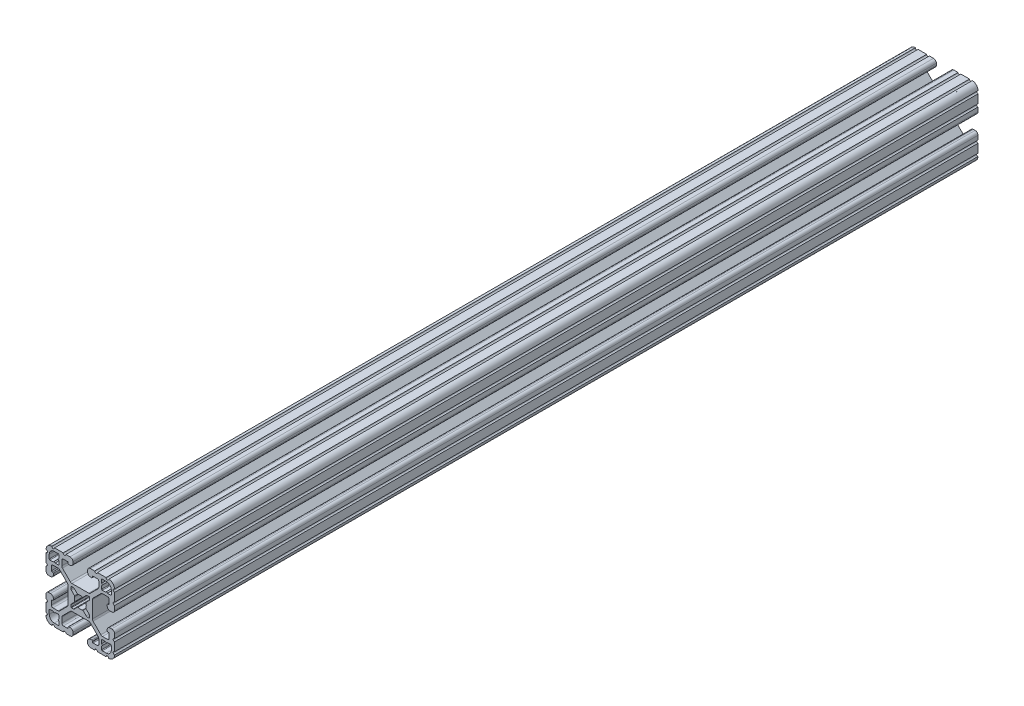
SolidWorks part; units mm, degrees
ref_plane "Front Plane" through (0, 0, 0) normal (0, 0, 1) x (1, 0, 0)
ref_plane "Top Plane" through (0, 0, 0) normal (0, 1, 0) x (1, 0, 0)
ref_plane "Right Plane" through (0, 0, 0) normal (1, 0, 0) x (0, 0, -1)
ref_plane "Plane1" through (0, 0, -304.8) normal (0, 0, -1) x (-1, 0, 0)
sketch "Sketch1" plane through (0, 0, -304.8) normal (0, 0, -1) x (-1, 0, 0)
  line L0 (-12.2479, 11.8669) -> (-14.0194, 11.8669)
  line L1 (-14.0212, 11.8676) -> (-14.5575, 12.4039)
  line L2 (-14.5611, 12.4039) -> (-15.0973, 11.8676)
  line L3 (-15.0991, 11.8669) -> (-16.8707, 11.8669)
  line L4 (-17.2517, 12.2479) -> (-17.2517, 14.4577)
  line L5 (-14.4577, 17.2517) -> (-12.2479, 17.2517)
  line L6 (-11.8669, 16.8707) -> (-11.8669, 15.0991)
  line L7 (-11.8676, 15.0973) -> (-12.4039, 14.5611)
  line L8 (-12.4039, 14.5575) -> (-11.8676, 14.0213)
  line L9 (-11.8669, 14.0195) -> (-11.8669, 12.2479)
  line L10 (-11.8669, -12.2479) -> (-11.8669, -14.0194)
  line L11 (-11.8676, -14.0212) -> (-12.4039, -14.5575)
  line L12 (-12.4039, -14.5611) -> (-11.8676, -15.0973)
  line L13 (-11.8669, -15.0991) -> (-11.8669, -16.8707)
  line L14 (-12.2479, -17.2517) -> (-14.4577, -17.2517)
  line L15 (-17.2517, -14.4577) -> (-17.2517, -12.2479)
  line L16 (-16.8707, -11.8669) -> (-15.0991, -11.8669)
  line L17 (-15.0973, -11.8676) -> (-14.5611, -12.4039)
  line L18 (-14.5575, -12.4039) -> (-14.0213, -11.8676)
  line L19 (-14.0195, -11.8669) -> (-12.2479, -11.8669)
  line L20 (12.2479, -11.8669) -> (14.0194, -11.8669)
  line L21 (14.0212, -11.8676) -> (14.5575, -12.4039)
  line L22 (14.5611, -12.4039) -> (15.0973, -11.8676)
  line L23 (15.0991, -11.8669) -> (16.8707, -11.8669)
  line L24 (17.2517, -12.2479) -> (17.2517, -14.4577)
  line L25 (14.4577, -17.2517) -> (12.2479, -17.2517)
  line L26 (11.8669, -16.8707) -> (11.8669, -15.0991)
  line L27 (11.8676, -15.0973) -> (12.4039, -14.5611)
  line L28 (12.4039, -14.5575) -> (11.8676, -14.0213)
  line L29 (11.8669, -14.0195) -> (11.8669, -12.2479)
  line L30 (11.8669, 12.2479) -> (11.8669, 14.0194)
  line L31 (11.8676, 14.0212) -> (12.4039, 14.5575)
  line L32 (12.4039, 14.5611) -> (11.8676, 15.0973)
  line L33 (11.8669, 15.0991) -> (11.8669, 16.8707)
  line L34 (12.2479, 17.2517) -> (14.4577, 17.2517)
  line L35 (17.2517, 14.4577) -> (17.2517, 12.2479)
  line L36 (16.8707, 11.8669) -> (15.0991, 11.8669)
  line L37 (15.0973, 11.8676) -> (14.5611, 12.4039)
  line L38 (14.5575, 12.4039) -> (14.0213, 11.8676)
  line L39 (14.0195, 11.8669) -> (12.2479, 11.8669)
  line L40 (1.5823, 3.1988) -> (3.2921, 4.9085)
  line L41 (3.9207, 5.1689) -> (4.9149, 5.1689)
  line L42 (5.1689, 4.9149) -> (5.1689, 3.9207)
  line L43 (4.9085, 3.2921) -> (3.1988, 1.5823)
  line L44 (3.1988, -1.5823) -> (4.9085, -3.2921)
  line L45 (5.1689, -3.9207) -> (5.1689, -4.9149)
  line L46 (4.9149, -5.1689) -> (3.9207, -5.1689)
  line L47 (3.2921, -4.9085) -> (1.5823, -3.1988)
  line L48 (-1.5823, -3.1988) -> (-3.2921, -4.9085)
  line L49 (-3.9207, -5.1689) -> (-4.9149, -5.1689)
  line L50 (-5.1689, -4.9149) -> (-5.1689, -3.9207)
  line L51 (-4.9085, -3.2921) -> (-3.1988, -1.5823)
  line L52 (-3.1988, 1.5823) -> (-4.9085, 3.2921)
  line L53 (-5.1689, 3.9207) -> (-5.1689, 4.9149)
  line L54 (-4.9149, 5.1689) -> (-3.9207, 5.1689)
  line L55 (-3.2921, 4.9085) -> (-1.5823, 3.1988)
  line L56 (-6.731, -15.3661) -> (-6.731, -15.6969)
  line L57 (-7.1122, -16.0782) -> (-9.3968, -16.0782)
  line L58 (-10.287, -15.1881) -> (-10.2871, -12.38)
  line L59 (-9.9142, -11.481) -> (-5.5384, -7.1147)
  line L60 (-4.6414, -6.7437) -> (4.6689, -6.7437)
  line L61 (5.5659, -7.1147) -> (9.9142, -11.4535)
  line L62 (10.2871, -12.3526) -> (10.287, -15.1881)
  line L63 (9.3968, -16.0782) -> (7.1122, -16.0782)
  line L64 (6.731, -15.6969) -> (6.731, -15.3661)
  line L65 (6.3498, -14.9848) -> (5.6531, -14.9848)
  line L66 (4.0778, -16.5601) -> (4.0778, -17.4747)
  line L67 (5.6531, -19.05) -> (7.9756, -19.05)
  line L68 (9.4996, -19.05) -> (14.3256, -19.05)
  line L69 (19.05, -14.2981) -> (19.05, -9.4996)
  line L70 (19.05, -7.9756) -> (19.05, -5.6531)
  line L71 (17.4747, -4.0778) -> (16.5601, -4.0778)
  line L72 (14.9848, -5.6531) -> (14.9848, -6.3498)
  line L73 (15.3661, -6.731) -> (15.6969, -6.731)
  line L74 (16.0782, -7.1122) -> (16.0782, -9.3968)
  line L75 (15.1881, -10.287) -> (12.38, -10.2871)
  line L76 (11.481, -9.9142) -> (7.1147, -5.5384)
  line L77 (6.7437, -4.6414) -> (6.7437, 4.6689)
  line L78 (7.1147, 5.5659) -> (11.4535, 9.9142)
  line L79 (12.3526, 10.2871) -> (15.1881, 10.287)
  line L80 (16.0782, 9.3968) -> (16.0782, 7.1122)
  line L81 (15.6969, 6.731) -> (15.3661, 6.731)
  line L82 (14.9848, 6.3498) -> (14.9848, 5.6531)
  line L83 (16.5601, 4.0778) -> (17.4747, 4.0778)
  line L84 (19.05, 5.6531) -> (19.05, 7.9756)
  line L85 (19.05, 9.4996) -> (19.05, 14.3256)
  line L86 (14.2981, 19.05) -> (9.4996, 19.05)
  line L87 (7.9756, 19.05) -> (5.6531, 19.05)
  line L88 (4.0778, 17.4747) -> (4.0778, 16.5601)
  line L89 (5.6531, 14.9848) -> (6.3498, 14.9848)
  line L90 (6.731, 15.3661) -> (6.731, 15.6969)
  line L91 (7.1122, 16.0782) -> (9.3968, 16.0782)
  line L92 (10.287, 15.1881) -> (10.2871, 12.38)
  line L93 (9.9142, 11.481) -> (5.5384, 7.1147)
  line L94 (4.6414, 6.7437) -> (-4.6689, 6.7437)
  line L95 (-5.5659, 7.1147) -> (-9.9142, 11.4535)
  line L96 (-10.2871, 12.3526) -> (-10.287, 15.1881)
  line L97 (-9.3968, 16.0782) -> (-7.1122, 16.0782)
  line L98 (-6.731, 15.6969) -> (-6.731, 15.3661)
  line L99 (-6.3498, 14.9848) -> (-5.6531, 14.9848)
  line L100 (-4.0778, 16.5601) -> (-4.0778, 17.4747)
  line L101 (-5.6531, 19.05) -> (-7.9756, 19.05)
  line L102 (-9.4996, 19.05) -> (-14.3256, 19.05)
  line L103 (-19.05, 14.2981) -> (-19.05, 9.4996)
  line L104 (-19.05, 7.9756) -> (-19.05, 5.6531)
  line L105 (-17.4747, 4.0778) -> (-16.5601, 4.0778)
  line L106 (-14.9848, 5.6531) -> (-14.9848, 6.3498)
  line L107 (-15.3661, 6.731) -> (-15.6969, 6.731)
  line L108 (-16.0782, 7.1122) -> (-16.0782, 9.3968)
  line L109 (-15.1881, 10.287) -> (-12.38, 10.2871)
  line L110 (-11.481, 9.9142) -> (-7.1147, 5.5384)
  line L111 (-6.7437, 4.6414) -> (-6.7437, -4.6689)
  line L112 (-7.1147, -5.5659) -> (-11.4535, -9.9142)
  line L113 (-12.3526, -10.2871) -> (-15.1881, -10.287)
  line L114 (-16.0782, -9.3968) -> (-16.0782, -7.1122)
  line L115 (-15.6969, -6.731) -> (-15.3661, -6.731)
  line L116 (-14.9848, -6.3498) -> (-14.9848, -5.6531)
  line L117 (-16.5601, -4.0778) -> (-17.4747, -4.0778)
  line L118 (-19.05, -5.6531) -> (-19.05, -7.9756)
  line L119 (-19.05, -9.4996) -> (-19.05, -14.3256)
  line L120 (-14.2981, -19.05) -> (-9.4996, -19.05)
  line L121 (-7.9756, -19.05) -> (-5.6531, -19.05)
  line L122 (-4.0778, -17.4747) -> (-4.0778, -16.5601)
  line L123 (-5.6531, -14.9848) -> (-6.3498, -14.9848)
  arc A0 (-14.0194, 11.8669) -> (-14.0212, 11.8676) centre (-14.0194, 11.8694) cw
  arc A1 (-14.5575, 12.4039) -> (-14.5611, 12.4039) centre (-14.5593, 12.4021) ccw
  arc A2 (-15.0973, 11.8676) -> (-15.0991, 11.8669) centre (-15.0991, 11.8694) cw
  arc A3 (-16.8707, 11.8669) -> (-17.2517, 12.2479) centre (-16.8707, 12.2479) cw
  arc A4 (-17.2517, 14.4577) -> (-14.4577, 17.2517) centre (-14.4577, 14.4577) cw
  arc A5 (-12.2479, 17.2517) -> (-11.8669, 16.8707) centre (-12.2479, 16.8707) cw
  arc A6 (-11.8669, 15.0991) -> (-11.8676, 15.0973) centre (-11.8694, 15.0991) cw
  arc A7 (-12.4039, 14.5611) -> (-12.4039, 14.5575) centre (-12.4021, 14.5593) ccw
  arc A8 (-11.8676, 14.0213) -> (-11.8669, 14.0195) centre (-11.8694, 14.0195) cw
  arc A9 (-11.8669, 12.2479) -> (-12.2479, 11.8669) centre (-12.2479, 12.2479) cw
  arc A10 (-11.8669, -14.0194) -> (-11.8676, -14.0212) centre (-11.8694, -14.0194) cw
  arc A11 (-12.4039, -14.5575) -> (-12.4039, -14.5611) centre (-12.4021, -14.5593) ccw
  arc A12 (-11.8676, -15.0973) -> (-11.8669, -15.0991) centre (-11.8694, -15.0991) cw
  arc A13 (-11.8669, -16.8707) -> (-12.2479, -17.2517) centre (-12.2479, -16.8707) cw
  arc A14 (-14.4577, -17.2517) -> (-17.2517, -14.4577) centre (-14.4577, -14.4577) cw
  arc A15 (-17.2517, -12.2479) -> (-16.8707, -11.8669) centre (-16.8707, -12.2479) cw
  arc A16 (-15.0991, -11.8669) -> (-15.0973, -11.8676) centre (-15.0991, -11.8694) cw
  arc A17 (-14.5611, -12.4039) -> (-14.5575, -12.4039) centre (-14.5593, -12.4021) ccw
  arc A18 (-14.0213, -11.8676) -> (-14.0195, -11.8669) centre (-14.0195, -11.8694) cw
  arc A19 (-12.2479, -11.8669) -> (-11.8669, -12.2479) centre (-12.2479, -12.2479) cw
  arc A20 (14.0194, -11.8669) -> (14.0212, -11.8676) centre (14.0194, -11.8694) cw
  arc A21 (14.5575, -12.4039) -> (14.5611, -12.4039) centre (14.5593, -12.4021) ccw
  arc A22 (15.0973, -11.8676) -> (15.0991, -11.8669) centre (15.0991, -11.8694) cw
  arc A23 (16.8707, -11.8669) -> (17.2517, -12.2479) centre (16.8707, -12.2479) cw
  arc A24 (17.2517, -14.4577) -> (14.4577, -17.2517) centre (14.4577, -14.4577) cw
  arc A25 (12.2479, -17.2517) -> (11.8669, -16.8707) centre (12.2479, -16.8707) cw
  arc A26 (11.8669, -15.0991) -> (11.8676, -15.0973) centre (11.8694, -15.0991) cw
  arc A27 (12.4039, -14.5611) -> (12.4039, -14.5575) centre (12.4021, -14.5593) ccw
  arc A28 (11.8676, -14.0213) -> (11.8669, -14.0195) centre (11.8694, -14.0195) cw
  arc A29 (11.8669, -12.2479) -> (12.2479, -11.8669) centre (12.2479, -12.2479) cw
  arc A30 (11.8669, 14.0194) -> (11.8676, 14.0212) centre (11.8694, 14.0194) cw
  arc A31 (12.4039, 14.5575) -> (12.4039, 14.5611) centre (12.4021, 14.5593) ccw
  arc A32 (11.8676, 15.0973) -> (11.8669, 15.0991) centre (11.8694, 15.0991) cw
  arc A33 (11.8669, 16.8707) -> (12.2479, 17.2517) centre (12.2479, 16.8707) cw
  arc A34 (14.4577, 17.2517) -> (17.2517, 14.4577) centre (14.4577, 14.4577) cw
  arc A35 (17.2517, 12.2479) -> (16.8707, 11.8669) centre (16.8707, 12.2479) cw
  arc A36 (15.0991, 11.8669) -> (15.0973, 11.8676) centre (15.0991, 11.8694) cw
  arc A37 (14.5611, 12.4039) -> (14.5575, 12.4039) centre (14.5593, 12.4021) ccw
  arc A38 (14.0213, 11.8676) -> (14.0195, 11.8669) centre (14.0195, 11.8694) cw
  arc A39 (12.2479, 11.8669) -> (11.8669, 12.2479) centre (12.2479, 12.2479) cw
  arc A40 (-1.5823, 3.1988) -> (-1.178, 3.1119) centre (-1.3129, 3.4682) ccw
  arc A41 (-1.178, 3.1119) -> (1.178, 3.1119) centre (0, 0) cw
  arc A42 (1.178, 3.1119) -> (1.5823, 3.1988) centre (1.3129, 3.4682) ccw
  arc A43 (3.2921, 4.9085) -> (3.9207, 5.1689) centre (3.9207, 4.2799) cw
  arc A44 (4.9149, 5.1689) -> (5.1689, 4.9149) centre (4.9149, 4.9149) cw
  arc A45 (5.1689, 3.9207) -> (4.9085, 3.2921) centre (4.2799, 3.9207) cw
  arc A46 (3.1988, 1.5823) -> (3.1119, 1.178) centre (3.4682, 1.3129) ccw
  arc A47 (3.1119, 1.178) -> (3.1119, -1.178) centre (0, 0) cw
  arc A48 (3.1119, -1.178) -> (3.1988, -1.5823) centre (3.4682, -1.3129) ccw
  arc A49 (4.9085, -3.2921) -> (5.1689, -3.9207) centre (4.2799, -3.9207) cw
  arc A50 (5.1689, -4.9149) -> (4.9149, -5.1689) centre (4.9149, -4.9149) cw
  arc A51 (3.9207, -5.1689) -> (3.2921, -4.9085) centre (3.9207, -4.2799) cw
  arc A52 (1.5823, -3.1988) -> (1.178, -3.1119) centre (1.3129, -3.4682) ccw
  arc A53 (1.178, -3.1119) -> (-1.178, -3.1119) centre (0, 0) cw
  arc A54 (-1.178, -3.1119) -> (-1.5823, -3.1988) centre (-1.3129, -3.4682) ccw
  arc A55 (-3.2921, -4.9085) -> (-3.9207, -5.1689) centre (-3.9207, -4.2799) cw
  arc A56 (-4.9149, -5.1689) -> (-5.1689, -4.9149) centre (-4.9149, -4.9149) cw
  arc A57 (-5.1689, -3.9207) -> (-4.9085, -3.2921) centre (-4.2799, -3.9207) cw
  arc A58 (-3.1988, -1.5823) -> (-3.1119, -1.178) centre (-3.4682, -1.3129) ccw
  arc A59 (-3.1119, -1.178) -> (-3.1119, 1.178) centre (0, 0) cw
  arc A60 (-3.1119, 1.178) -> (-3.1988, 1.5823) centre (-3.4682, 1.3129) ccw
  arc A61 (-4.9085, 3.2921) -> (-5.1689, 3.9207) centre (-4.2799, 3.9207) cw
  arc A62 (-5.1689, 4.9149) -> (-4.9149, 5.1689) centre (-4.9149, 4.9149) cw
  arc A63 (-3.9207, 5.1689) -> (-3.2921, 4.9085) centre (-3.9207, 4.2799) cw
  arc A64 (-6.3498, -14.9848) -> (-6.731, -15.3661) centre (-6.35, -15.3658) ccw
  arc A65 (-6.731, -15.6969) -> (-7.1122, -16.0782) centre (-7.112, -15.6972) cw
  arc A66 (-9.3968, -16.0782) -> (-10.287, -15.1881) centre (-9.398, -15.1892) cw
  arc A67 (-10.2871, -12.38) -> (-9.9142, -11.481) centre (-9.0171, -12.38) cw
  arc A68 (-5.5384, -7.1147) -> (-4.6414, -6.7437) centre (-4.6414, -8.0137) cw
  arc A69 (4.6689, -6.7437) -> (5.5659, -7.1147) centre (4.6689, -8.0137) cw
  arc A70 (9.9142, -11.4535) -> (10.2871, -12.3526) centre (9.0171, -12.3525) cw
  arc A71 (10.287, -15.1881) -> (9.3968, -16.0782) centre (9.398, -15.1892) cw
  arc A72 (7.1122, -16.0782) -> (6.731, -15.6969) centre (7.112, -15.6972) cw
  arc A73 (6.731, -15.3661) -> (6.3498, -14.9848) centre (6.35, -15.3658) ccw
  arc A74 (5.6531, -14.9848) -> (4.0778, -16.5601) centre (5.6526, -16.5596) ccw
  arc A75 (4.0778, -17.4747) -> (5.6531, -19.05) centre (5.6526, -17.4752) ccw
  arc A76 (7.9756, -19.05) -> (9.4996, -19.05) centre (8.7376, -19.05) cw
  arc A77 (14.3256, -19.05) -> (15.8496, -19.0499) centre (15.0876, -19.05) cw
  arc A78 (15.8496, -19.0499) -> (19.0496, -15.8221) centre (15.875, -15.875) ccw
  arc A79 (19.0496, -15.8221) -> (19.05, -14.2981) centre (19.05, -15.0601) cw
  arc A80 (19.05, -9.4996) -> (19.05, -7.9756) centre (19.05, -8.7376) cw
  arc A81 (19.05, -5.6531) -> (17.4747, -4.0778) centre (17.4752, -5.6526) ccw
  arc A82 (16.5601, -4.0778) -> (14.9848, -5.6531) centre (16.5596, -5.6526) ccw
  arc A83 (14.9848, -6.3498) -> (15.3661, -6.731) centre (15.3658, -6.35) ccw
  arc A84 (15.6969, -6.731) -> (16.0782, -7.1122) centre (15.6972, -7.112) cw
  arc A85 (16.0782, -9.3968) -> (15.1881, -10.287) centre (15.1892, -9.398) cw
  arc A86 (12.38, -10.2871) -> (11.481, -9.9142) centre (12.38, -9.0171) cw
  arc A87 (7.1147, -5.5384) -> (6.7437, -4.6414) centre (8.0137, -4.6414) cw
  arc A88 (6.7437, 4.6689) -> (7.1147, 5.5659) centre (8.0137, 4.6689) cw
  arc A89 (11.4535, 9.9142) -> (12.3526, 10.2871) centre (12.3525, 9.0171) cw
  arc A90 (15.1881, 10.287) -> (16.0782, 9.3968) centre (15.1892, 9.398) cw
  arc A91 (16.0782, 7.1122) -> (15.6969, 6.731) centre (15.6972, 7.112) cw
  arc A92 (15.3661, 6.731) -> (14.9848, 6.3498) centre (15.3658, 6.35) ccw
  arc A93 (14.9848, 5.6531) -> (16.5601, 4.0778) centre (16.5596, 5.6526) ccw
  arc A94 (17.4747, 4.0778) -> (19.05, 5.6531) centre (17.4752, 5.6526) ccw
  arc A95 (19.05, 7.9756) -> (19.05, 9.4996) centre (19.05, 8.7376) cw
  arc A96 (19.05, 14.3256) -> (19.0499, 15.8496) centre (19.05, 15.0876) cw
  arc A97 (19.0499, 15.8496) -> (15.8221, 19.0496) centre (15.875, 15.875) ccw
  arc A98 (15.8221, 19.0496) -> (14.2981, 19.05) centre (15.0601, 19.05) cw
  arc A99 (9.4996, 19.05) -> (7.9756, 19.05) centre (8.7376, 19.05) cw
  arc A100 (5.6531, 19.05) -> (4.0778, 17.4747) centre (5.6526, 17.4752) ccw
  arc A101 (4.0778, 16.5601) -> (5.6531, 14.9848) centre (5.6526, 16.5596) ccw
  arc A102 (6.3498, 14.9848) -> (6.731, 15.3661) centre (6.35, 15.3658) ccw
  arc A103 (6.731, 15.6969) -> (7.1122, 16.0782) centre (7.112, 15.6972) cw
  arc A104 (9.3968, 16.0782) -> (10.287, 15.1881) centre (9.398, 15.1892) cw
  arc A105 (10.2871, 12.38) -> (9.9142, 11.481) centre (9.0171, 12.38) cw
  arc A106 (5.5384, 7.1147) -> (4.6414, 6.7437) centre (4.6414, 8.0137) cw
  arc A107 (-4.6689, 6.7437) -> (-5.5659, 7.1147) centre (-4.6689, 8.0137) cw
  arc A108 (-9.9142, 11.4535) -> (-10.2871, 12.3526) centre (-9.0171, 12.3525) cw
  arc A109 (-10.287, 15.1881) -> (-9.3968, 16.0782) centre (-9.398, 15.1892) cw
  arc A110 (-7.1122, 16.0782) -> (-6.731, 15.6969) centre (-7.112, 15.6972) cw
  arc A111 (-6.731, 15.3661) -> (-6.3498, 14.9848) centre (-6.35, 15.3658) ccw
  arc A112 (-5.6531, 14.9848) -> (-4.0778, 16.5601) centre (-5.6526, 16.5596) ccw
  arc A113 (-4.0778, 17.4747) -> (-5.6531, 19.05) centre (-5.6526, 17.4752) ccw
  arc A114 (-7.9756, 19.05) -> (-9.4996, 19.05) centre (-8.7376, 19.05) cw
  arc A115 (-14.3256, 19.05) -> (-15.8496, 19.0499) centre (-15.0876, 19.05) cw
  arc A116 (-15.8496, 19.0499) -> (-19.0496, 15.8221) centre (-15.875, 15.875) ccw
  arc A117 (-19.0496, 15.8221) -> (-19.05, 14.2981) centre (-19.05, 15.0601) cw
  arc A118 (-19.05, 9.4996) -> (-19.05, 7.9756) centre (-19.05, 8.7376) cw
  arc A119 (-19.05, 5.6531) -> (-17.4747, 4.0778) centre (-17.4752, 5.6526) ccw
  arc A120 (-16.5601, 4.0778) -> (-14.9848, 5.6531) centre (-16.5596, 5.6526) ccw
  arc A121 (-14.9848, 6.3498) -> (-15.3661, 6.731) centre (-15.3658, 6.35) ccw
  arc A122 (-15.6969, 6.731) -> (-16.0782, 7.1122) centre (-15.6972, 7.112) cw
  arc A123 (-16.0782, 9.3968) -> (-15.1881, 10.287) centre (-15.1892, 9.398) cw
  arc A124 (-12.38, 10.2871) -> (-11.481, 9.9142) centre (-12.38, 9.0171) cw
  arc A125 (-7.1147, 5.5384) -> (-6.7437, 4.6414) centre (-8.0137, 4.6414) cw
  arc A126 (-6.7437, -4.6689) -> (-7.1147, -5.5659) centre (-8.0137, -4.6689) cw
  arc A127 (-11.4535, -9.9142) -> (-12.3526, -10.2871) centre (-12.3525, -9.0171) cw
  arc A128 (-15.1881, -10.287) -> (-16.0782, -9.3968) centre (-15.1892, -9.398) cw
  arc A129 (-16.0782, -7.1122) -> (-15.6969, -6.731) centre (-15.6972, -7.112) cw
  arc A130 (-15.3661, -6.731) -> (-14.9848, -6.3498) centre (-15.3658, -6.35) ccw
  arc A131 (-14.9848, -5.6531) -> (-16.5601, -4.0778) centre (-16.5596, -5.6526) ccw
  arc A132 (-17.4747, -4.0778) -> (-19.05, -5.6531) centre (-17.4752, -5.6526) ccw
  arc A133 (-19.05, -7.9756) -> (-19.05, -9.4996) centre (-19.05, -8.7376) cw
  arc A134 (-19.05, -14.3256) -> (-19.0499, -15.8496) centre (-19.05, -15.0876) cw
  arc A135 (-19.0499, -15.8496) -> (-15.8221, -19.0496) centre (-15.875, -15.875) ccw
  arc A136 (-15.8221, -19.0496) -> (-14.2981, -19.05) centre (-15.0601, -19.05) cw
  arc A137 (-9.4996, -19.05) -> (-7.9756, -19.05) centre (-8.7376, -19.05) cw
  arc A138 (-5.6531, -19.05) -> (-4.0778, -17.4747) centre (-5.6526, -17.4752) ccw
  arc A139 (-4.0778, -16.5601) -> (-5.6531, -14.9848) centre (-5.6526, -16.5596) ccw
extrude "Boss-Extrude1" add sketch "Sketch1" against normal blind 480
